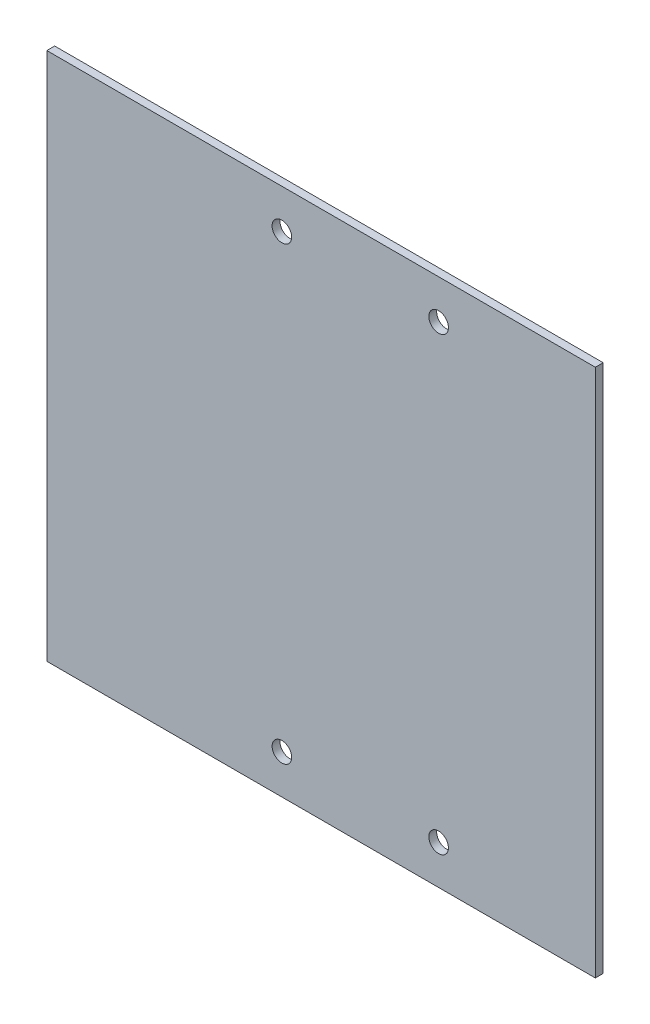
SolidWorks part; units mm, degrees
ref_plane "Ön Düzlem" through (0, 0, 0) normal (0, 0, 1) x (1, 0, 0)
ref_plane "Üst Düzlem" through (0, 0, 0) normal (0, 1, 0) x (1, 0, 0)
ref_plane "Sağ Düzlem" through (0, 0, 0) normal (1, 0, 0) x (0, 0, -1)
sketch "Çizim1" plane through (0, 0, 0) normal (0, 0, 1) x (1, 0, 0)
  line L0 (60, 135) -> (60, 0) construction
  line L1 (0, 0) -> (140, 0)
  line L2 (0, 0) -> (0, 135)
  line L3 (0, 135) -> (140, 135)
  line L4 (140, 0) -> (140, 135)
  line L5 (100, 135) -> (100, 0) construction
  line L6 (0, 125) -> (140, 125) construction
  line L7 (0, 10) -> (140, 10) construction
  circle A0 centre (60, 125) radius 2.5
  circle A1 centre (100, 125) radius 2.5
  circle A2 centre (60, 10) radius 2.5
  circle A3 centre (100, 10) radius 2.5
  dimension "D6" = 10
  dimension "D8" = 5
  dimension "D1" = 60
  dimension "D2" = 40
  dimension "D3" = 10
  dimension "D4" = 10
  dimension "D5" = 135
  dimension "D7" = 140
extrude "Yükseklik-Ekstrüzyon1" add sketch "Çizim1" along normal blind 2
